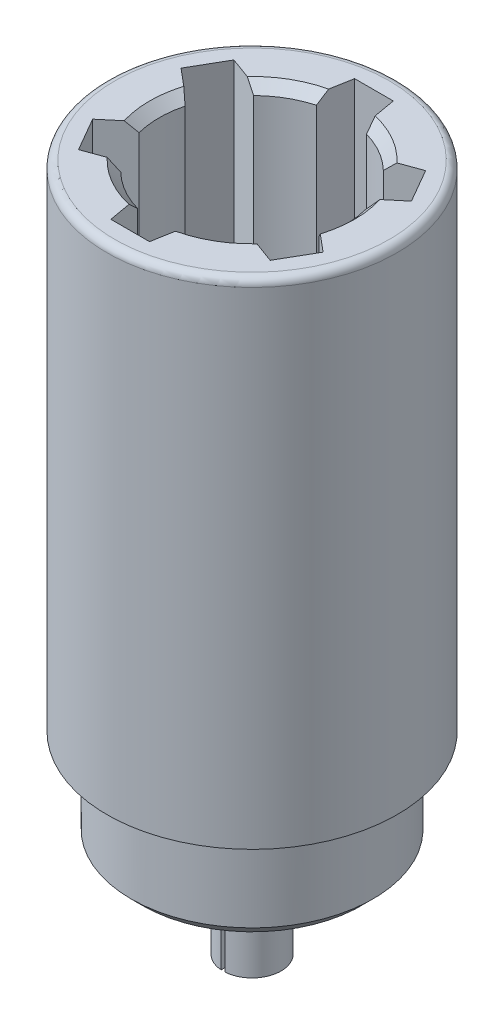
SolidWorks part; units mm, degrees
material "6061 Alloy"
ref_plane "Front" through (0, 0, 0) normal (0, 0, 1) x (1, 0, 0)
ref_plane "Top" through (0, 0, 0) normal (0, 1, 0) x (1, 0, 0)
ref_plane "Right" through (0, 0, 0) normal (1, 0, 0) x (0, 0, -1)
sketch "Sketch1" plane through (0, 0, 0) normal (1, 0, 0) x (0, 0, -1)
  line L0 (-6.096, 38.1) -> (-6.096, 8.706)
  line L1 (-6.096, 8.706) -> (0, 0)
  line L2 (0, 0) -> (0, 26.3018) construction
  line L3 (-6.096, 38.1) -> (-9.525, 38.1)
  line L4 (-9.525, 38.1) -> (-9.525, 5.6429)
  line L5 (-9.525, 5.6429) -> (-7.9375, 5.6429)
  line L6 (0, -7.0571) -> (0, 0)
  line L7 (-7.9375, 5.6429) -> (-7.9375, -0.7071)
  line L8 (-7.9375, -0.7071) -> (-1.905, -0.7071)
  line L9 (-1.905, -0.7071) -> (-1.905, -7.0571)
  line L10 (-1.905, -7.0571) -> (0, -7.0571)
  circle A0 centre (0, 0) radius 2.032 construction
  dimension "D9" = 4.064
  dimension "D1" = 35
  dimension "D2" = 12.192
  dimension "D3" = 15.875
  dimension "D4" = 19.05
  dimension "D5" = 38.1
  dimension "D6" = 3.81
  dimension "D7" = 6.35
  dimension "D8" = 6.35
revolve "mainBody" add sketch "Sketch1" angle 360 about L2
chamfer "Chamfer1" distance 0.635 angle 45 1 edges at (0, 38.1, -6.096)
fillet "Fillet3" radius 0.508 1 edges at (0, 38.1, -9.525)
sketch "Sketch13" plane through (0, 38.1, 0) normal (0, 1, 0) x (1, 0, 0)
  line L0 (-1.27, 8.001) -> (1.27, 8.001)
  line L1 (1.27, 8.001) -> (2.2759, 2.2963)
  line L2 (2.2759, 2.2963) -> (-2.2759, 2.2963)
  line L3 (-2.2759, 2.2963) -> (-1.27, 8.001)
  line L5 (0, 8.001) -> (0, 2.2963) construction
  circle A0 centre (0, 0) radius 6.731 construction
  point P5 (0, 6.731)
  dimension "D2" = 2.54
  dimension "D3" = 80
  dimension "D4" = 1.27
extrude "Cut-Extrude8" cut sketch "Sketch13" against normal up to surface (33.4827 mm away)
pattern_circular "CirPattern1" count 6 over 360 about axis through (0, 0, 0) along (0, 1, 0) of "Cut-Extrude8"
fillet "Fillet4" radius 0.762 1 edges at (0, -0.7071, -1.905)
sketch "Sketch15" plane through (0, 0, 0) normal (0, 0, 1) x (1, 0, 0)
  line L0 (-1.905, -0.7071) -> (1.905, -0.7071) construction
  line L1 (-0.127, -25.872) -> (0.127, -25.872)
  line L2 (-0.127, -25.872) -> (-0.127, -0.7071)
  line L3 (-0.127, -0.7071) -> (0.127, -0.7071)
  line L4 (0.127, -25.872) -> (0.127, -0.7071)
  line L5 (-0.127, -25.872) -> (0.127, -0.7071) construction
  line L6 (-0.127, -0.7071) -> (0.127, -25.872) construction
  point P0 (0, -13.2896)
  dimension "D1" = 0.254
extrude "Cut-Extrude9" cut sketch "Sketch15" against normal through all and the other way through all
chamfer "Chamfer2" distance 0.762 angle 45 1 edges at (0, -0.7071, -7.9375)
